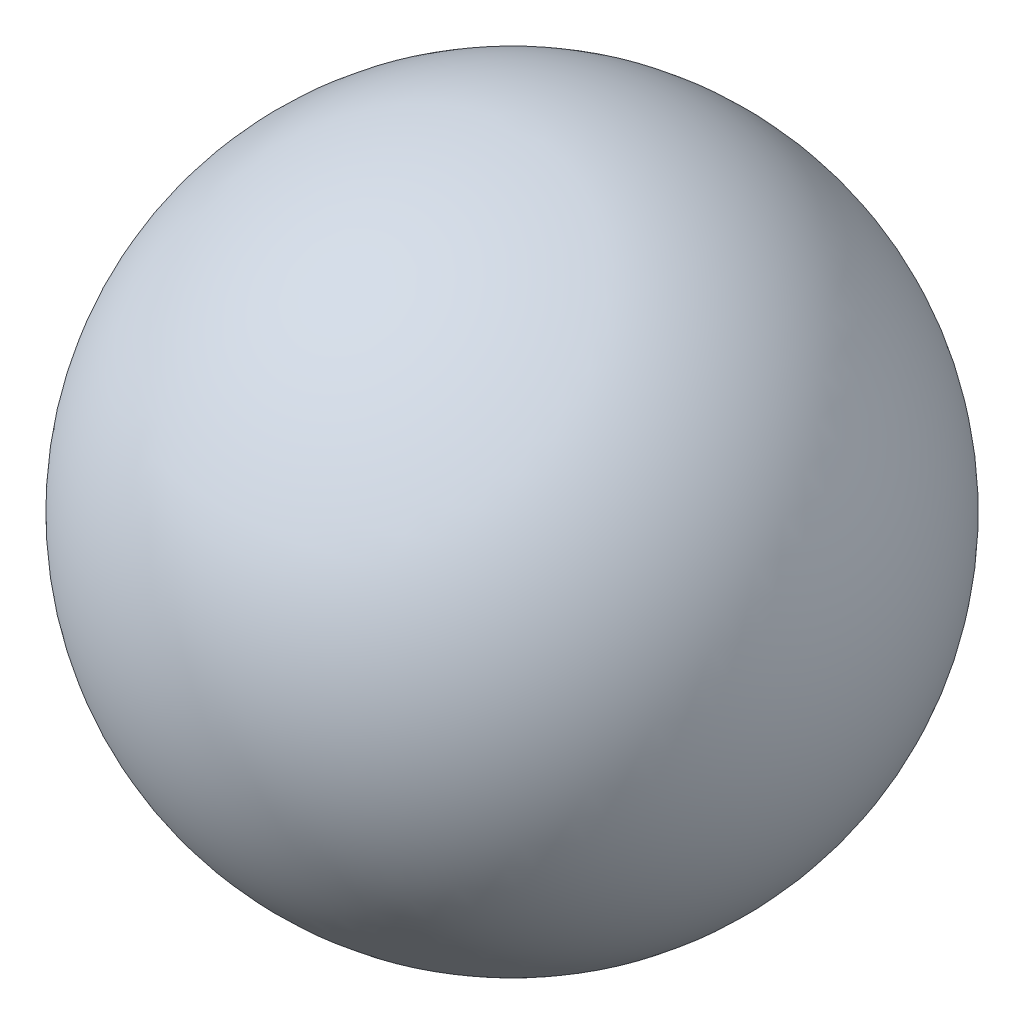
SolidWorks part; units mm, degrees
ref_plane "前视基准面" through (0, 0, 0) normal (0, 0, 1) x (1, 0, 0)
ref_plane "上视基准面" through (0, 0, 0) normal (0, 1, 0) x (1, 0, 0)
ref_plane "右视基准面" through (0, 0, 0) normal (1, 0, 0) x (0, 0, -1)
sketch "草图1" plane through (0, 0, 0) normal (1, 0, 0) x (0, 0, -1)
  line L0 (0, -10) -> (0, 20)
  arc A0 (0, -10) -> (0, 20) centre (0, 5) ccw
revolve "旋转1" add sketch "草图1" angle 360 about L0
